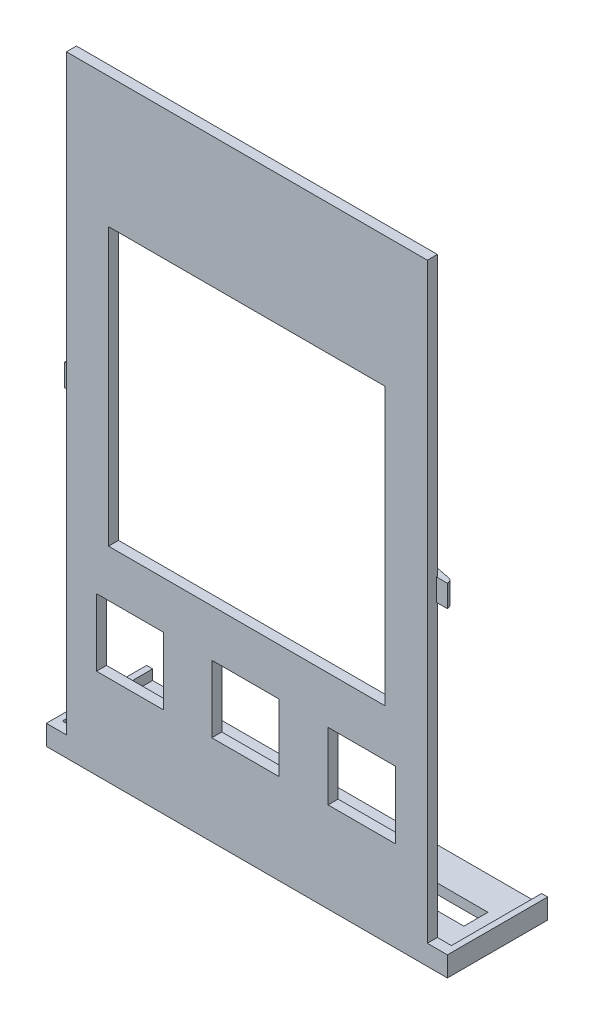
SolidWorks part; units mm, degrees
ref_plane "前视基准面" through (0, 0, 0) normal (0, 0, 1) x (1, 0, 0)
ref_plane "上视基准面" through (0, 0, 0) normal (0, 1, 0) x (1, 0, 0)
ref_plane "右视基准面" through (0, 0, 0) normal (1, 0, 0) x (0, 0, -1)
sketch "草图1" plane through (0, 0, 0) normal (0, 0, 1) x (1, 0, 0)
  line L1 (-20, 31) -> (20, 31)
  line L2 (-20, 31) -> (-20, -31)
  line L3 (-20, -31) -> (20, -31)
  line L4 (20, 31) -> (20, -31)
  line L5 (-20, 31) -> (20, -31) construction
  line L6 (-20, -31) -> (20, 31) construction
  point P0 (0, 0)
  dimension "D1" = 40
  dimension "D2" = 62
extrude "凸台-拉伸1" add sketch "草图1" along normal blind 1
sketch "草图3" plane through (0, 0, 1) normal (0, 0, 1) x (1, 0, 0)
  line L0 (0, -1000) -> (0, 49000) construction
  line L1 (-13.8, 16) -> (13.8, 16)
  line L2 (-13.8, 16) -> (-13.8, -11.6)
  line L3 (-13.8, -11.6) -> (13.8, -11.6)
  line L4 (13.8, 16) -> (13.8, -11.6)
  line L5 (-13.8, 16) -> (13.8, -11.6) construction
  line L6 (-13.8, -11.6) -> (13.8, 16) construction
  line L7 (20, 31) -> (-20, 31) construction
  line L8 (-20, -31) -> (20, -31) construction
  line L9 (-15, -16.3) -> (-8.3, -16.3)
  line L10 (-15, -16.3) -> (-15, -23)
  line L11 (-15, -23) -> (-8.3, -23)
  line L12 (-8.3, -16.3) -> (-8.3, -23)
  line L13 (-15, -16.3) -> (-8.3, -23) construction
  line L14 (-15, -23) -> (-8.3, -16.3) construction
  line L15 (-20, 31) -> (-20, -31) construction
  line L16 (-3.5, -16.3) -> (3.2, -16.3)
  line L17 (-3.5, -16.3) -> (-3.5, -23)
  line L18 (-3.5, -23) -> (3.2, -23)
  line L19 (3.2, -16.3) -> (3.2, -23)
  line L20 (-3.5, -16.3) -> (3.2, -23) construction
  line L21 (-3.5, -23) -> (3.2, -16.3) construction
  line L22 (8.1, -16.3) -> (14.8, -16.3)
  line L23 (8.1, -16.3) -> (8.1, -23)
  line L24 (8.1, -23) -> (14.8, -23)
  line L25 (14.8, -16.3) -> (14.8, -23)
  line L26 (8.1, -16.3) -> (14.8, -23) construction
  line L27 (8.1, -23) -> (14.8, -16.3) construction
  point P0 (0, 2.2)
  point P11 (-11.65, -19.65)
  point P24 (11.45, -19.65)
  dimension "D1" = 27.6
  dimension "D2" = 27.6
  dimension "D3" = 15
  dimension "D4" = 8
  dimension "D5" = 6.7
  dimension "D6" = 6.7
  dimension "D7" = 4.8
  dimension "D8" = 6.7
  dimension "D9" = 6.7
  dimension "D10" = 6.7
  dimension "D11" = 6.7
  dimension "D12" = 4.9
  dimension "D13" = 5
extrude "切除-拉伸1" cut sketch "草图3" against normal through all
sketch "草图4" plane through (0, 0, 0) normal (0, 0, -1) x (-1, 0, 0)
  line L0 (0, 70.7152) -> (0, -35.7152) construction
  line L6 (-16.9, 22.5274) -> (-16.2, 22.5274)
  line L7 (-16.9, 22.5274) -> (-16.9, -14.3)
  line L8 (-16.9, -14.3) -> (-15.9, -14.3)
  line L9 (-16.2, 22.5274) -> (-16.2, -13.6)
  line L11 (-15.9, -14.3) -> (15.9, -14.3)
  line L13 (-16.2, -13.6) -> (16.2, -13.6)
  line L15 (13.8, -11.6) -> (-13.8, -11.6) construction
  line L17 (16.2, 22.5274) -> (16.2, -13.6)
  line L18 (16.9, -14.3) -> (15.9, -14.3)
  line L19 (16.9, 22.5274) -> (16.9, -14.3)
  line L20 (16.9, 22.5274) -> (16.2, 22.5274)
  point P3 (0, 17.5)
  point P9 (-14.8, 26.5)
  point P10 (14.8, 26.5)
  point P16 (0, -13.6)
  point P17 (0, -14.3)
  dimension "D1" = 16.2
  dimension "D2" = 0.7
  dimension "D3" = 0.7
  dimension "D4" = 2
extrude "凸台-拉伸2" add sketch "草图4" along normal blind 1
sketch "草图8" plane through (0, -31, 0) normal (0, -1, 0) x (1, 0, 0)
  line L1 (-20, 1) -> (20, 1)
  line L2 (-20, 1) -> (-20, 0)
  line L3 (-20, 0) -> (20, 0)
  line L4 (20, 1) -> (20, 0)
extrude "凸台-拉伸5" add sketch "草图8" along normal blind 1
sketch "草图10" plane through (0, 0, 0) normal (0, 0, -1) x (-1, 0, 0)
  line L0 (0, -1000) -> (0, 49000) construction
  line L1 (-20, -32) -> (-19.4, -32)
  line L2 (-20, -32) -> (-20, -30)
  line L3 (-20, -30) -> (-19.4, -30)
  line L4 (-19.4, -32) -> (-19.4, -30)
  line L5 (19.4, -32) -> (19.4, -30)
  line L6 (20, -30) -> (19.4, -30)
  line L7 (20, -32) -> (20, -30)
  line L8 (20, -32) -> (19.4, -32)
  dimension "D1" = 2
  dimension "D2" = 0.6
extrude "凸台-拉伸6" add sketch "草图10" along normal blind 9
sketch "草图11" plane through (0, 0, 0) normal (0, 0, -1) x (-1, 0, 0)
  line L0 (19.4, -30) -> (19.4, -32) construction
  line L1 (-19.4, -32) -> (19.4, -32)
  line L2 (-19.4, -32) -> (-19.4, -31)
  line L3 (-19.4, -31) -> (19.4, -31)
  line L4 (19.4, -32) -> (19.4, -31)
extrude "凸台-拉伸7" add sketch "草图11" along normal blind 9
sketch "草图13" plane through (0, -32, 0) normal (0, -1, 0) x (1, 0, 0)
  line L0 (20, -9) -> (-20, -9) construction
  line L1 (-18.1543, -3.3) -> (-10.9543, -3.3)
  line L2 (-18.1543, -3.3) -> (-18.1543, -5.5)
  line L3 (-18.1543, -5.5) -> (-10.9543, -5.5)
  line L4 (-10.9543, -3.3) -> (-10.9543, -5.5)
  line L5 (-20, 1) -> (-20, -9) construction
  line L7 (-9.1543, -7) -> (0.2457, -7)
  line L8 (-9.1543, -7) -> (-9.1543, -3.2)
  line L9 (-9.1543, -3.2) -> (0.2457, -3.2)
  line L10 (0.2457, -7) -> (0.2457, -3.2)
  line L11 (2.3457, -5.7) -> (17.3457, -5.7)
  line L12 (2.3457, -5.7) -> (2.3457, -3.3)
  line L13 (2.3457, -3.3) -> (17.3457, -3.3)
  line L14 (17.3457, -5.7) -> (17.3457, -3.3)
  dimension "D1" = 3.5
  dimension "D2" = 1.8457
  dimension "D3" = 2.2
  dimension "D4" = 7.2
  dimension "D5" = 2
  dimension "D6" = 1.8
  dimension "D7" = 3.8
  dimension "D8" = 9.4
  dimension "D9" = 3.3
  dimension "D10" = 2.1
  dimension "D11" = 15
  dimension "D12" = 2.4
extrude "切除-拉伸2" cut sketch "草图13" against normal up to next
sketch "草图14" plane through (0, 0, 1) normal (0, 0, 1) x (1, 0, 0)
  line L0 (20, -32) -> (-20, -32) construction
  line L1 (-20, 31) -> (-18, 31)
  line L2 (-20, 31) -> (-20, -30)
  line L3 (-20, -30) -> (-18, -30)
  line L4 (-18, 29) -> (-18, -30)
  line L5 (0, -1000) -> (0, 49000) construction
  line L6 (18, 29) -> (18, -30)
  line L7 (20, -30) -> (18, -30)
  line L8 (20, 31) -> (20, -30)
  line L9 (20, 31) -> (18, 31)
  line L11 (-18, 31) -> (18, 31)
  line L13 (-18, 29) -> (18, 29)
  dimension "D1" = 2
  dimension "D2" = 2
  dimension "D3" = 2
extrude "切除-拉伸3" cut sketch "草图14" against normal blind 10
sketch "草图15" plane through (-16.9, 0, 0) normal (-1, 0, 0) x (0, 0, 1)
  line L0 (0.1, 1.45) -> (0.1, -1.25) construction
  line L1 (-0.7919, 1.2) -> (0.1, 1.2)
  line L2 (-0.7919, 1.2) -> (-0.7919, -1)
  line L3 (-0.7919, -1) -> (0.1, -1)
  line L4 (0.1, 1.2) -> (0.1, -1)
  line L5 (0.1, 1.45) -> (-1.1, 1.45) construction
  line L6 (0.1, -1.25) -> (-1.1, -1.25) construction
  dimension "D1" = 0.25
  dimension "D2" = 0.25
extrude "凸台-拉伸8" add sketch "草图15" along normal blind 2.2
sketch "草图16" plane through (0, 1.2, 0) normal (0, 1, 0) x (1, 0, 0)
  line L0 (-16.9, 0.7919) -> (-19.1, 0.346)
  line L1 (-19.1, -0.1) -> (-19.1, 0.7919) construction
  line L2 (-19.1, 0.346) -> (-19.1, 0.7919)
  line L3 (-19.1, 0.7919) -> (-16.9, 0.7919)
extrude "切除-拉伸4" cut sketch "草图16" against normal up to next
fillet "圆角1" radius 0.5 1 edges at (-19.1, 0.1, -0.346)
mirror "镜向1" about plane through (0, 0, 0) normal (1, 0, 0) of "凸台-拉伸8", "切除-拉伸4", "圆角1"
